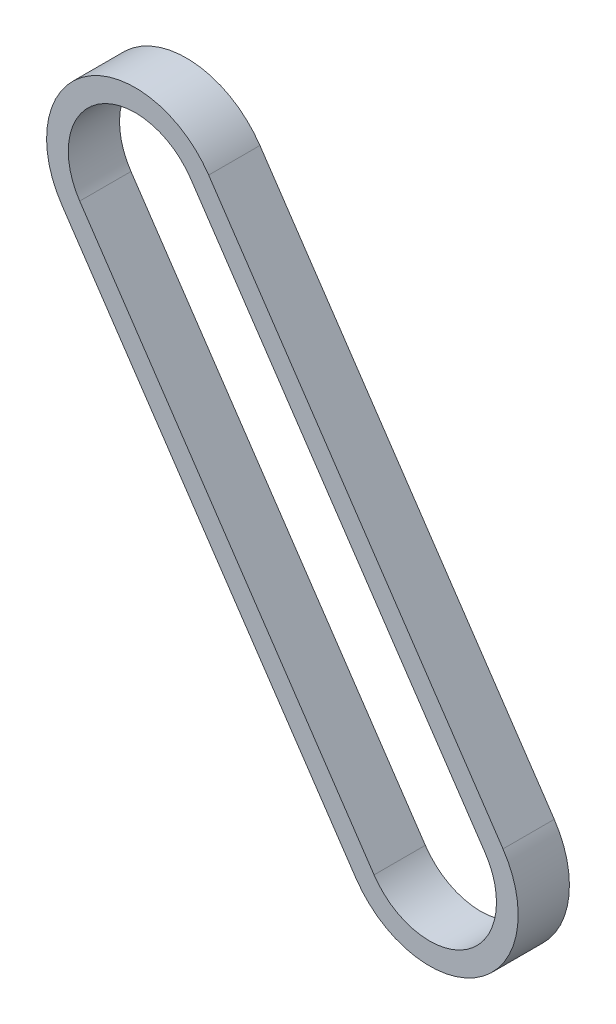
SolidWorks part; units mm, degrees
ref_plane "Front Plane" through (0, 0, 0) normal (0, 0, 1) x (1, 0, 0)
ref_plane "Top Plane" through (0, 0, 0) normal (0, 1, 0) x (1, 0, 0)
ref_plane "Right Plane" through (0, 0, 0) normal (1, 0, 0) x (0, 0, -1)
sketch "Sketch2" plane through (0, 0, 0) normal (0, 0, 1) x (1, 0, 0)
  line L0 (0, 0) -> (1, 0) construction
  line L1 (0, 0) -> (0, 1) construction
  line L2 (-11.4682, -7.7354) -> (-63.158, 68.898)
  line L3 (-40.2217, 84.3687) -> (11.4682, 7.7354)
  arc A0 (11.4682, 7.7354) -> (-11.4682, -7.7354) centre (0, 0) cw
  arc A1 (-63.158, 68.898) -> (-40.2217, 84.3687) centre (-51.6898, 76.6333) cw
extrude "Extrude-Thin1" add sketch "Sketch2" along normal mid plane 9 thin thin type two direction wall 1.73 second wall 2.08
